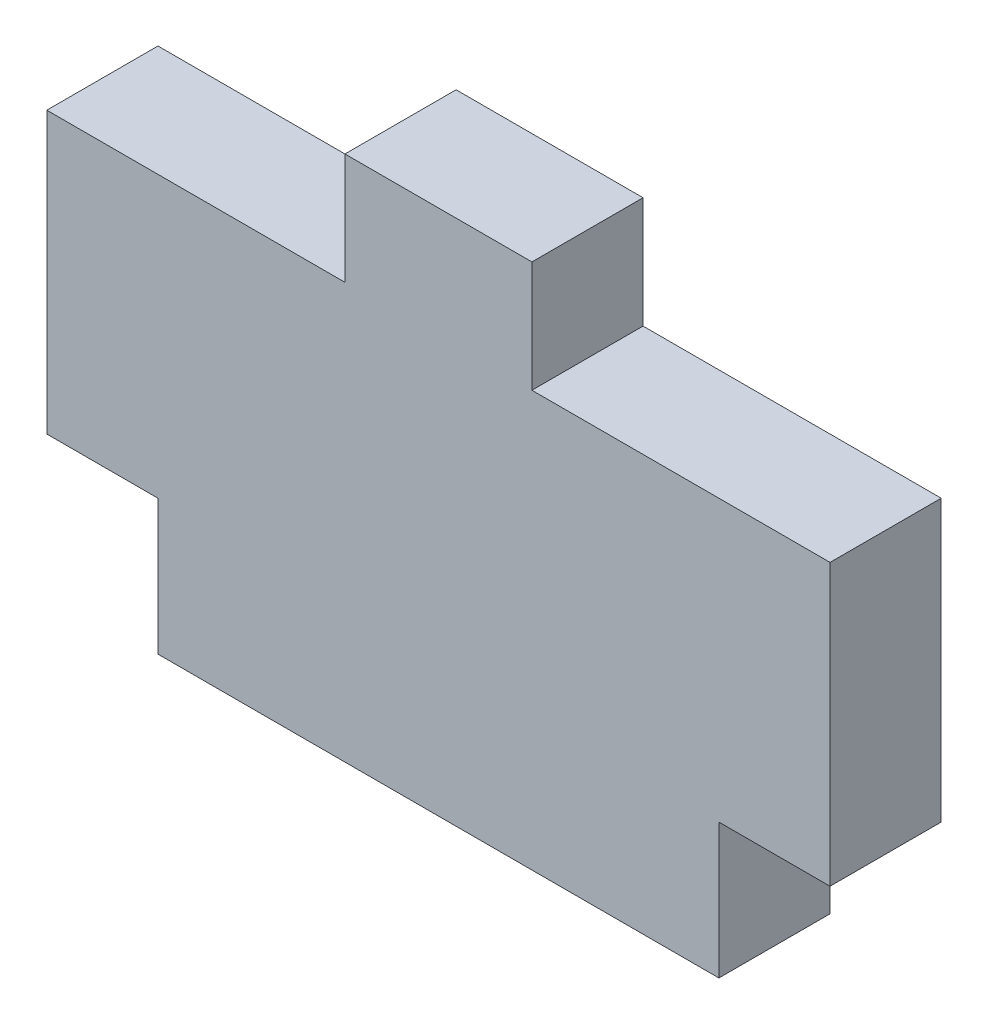
SolidWorks part; units mm, degrees
ref_plane "Front Plane" through (0, 0, 0) normal (0, 0, 1) x (1, 0, 0)
ref_plane "Top Plane" through (0, 0, 0) normal (0, 1, 0) x (1, 0, 0)
ref_plane "Right Plane" through (0, 0, 0) normal (1, 0, 0) x (0, 0, -1)
sketch "Model" plane through (0, 0, 0) normal (0, 0, 1) x (1, 0, 0)
  line L0 (4.5, 20) -> (18.85, 20)
  line L1 (-13.5, 0) -> (13.5, 0)
  line L2 (-18.85, 6.5) -> (-18.85, 20)
  line L3 (-18.85, 20) -> (-4.5, 20)
  line L4 (18.85, 6.5) -> (18.85, 20)
  line L5 (-18.85, 6.5) -> (-13.5, 6.5)
  line L8 (-13.5, 6.5) -> (-13.5, 0)
  line L9 (18.85, 6.5) -> (13.5, 6.5)
  line L12 (13.5, 6.5) -> (13.5, 0)
  line L14 (-4.5, 20) -> (-4.5, 25.35)
  line L15 (-4.5, 25.35) -> (4.5, 25.35)
  line L16 (4.5, 20) -> (4.5, 25.35)
  dimension "D2" = 9
  dimension "D3" = 37.7
  dimension "D6" = 20
  dimension "D8" = 13.5
  dimension "D11" = 5.35
  dimension "D9" = 5.35
extrude "Boss-Extrude1" add sketch "Model" along normal blind 5.35
equation "\"mdfthick\"=5.35"
equation "\"D11@Model\"=\"mdfthick\""
equation "\"D9@Model\"=\"mdfthick\""
equation "\"D1@Boss-Extrude1\"=\"mdfthick\""
